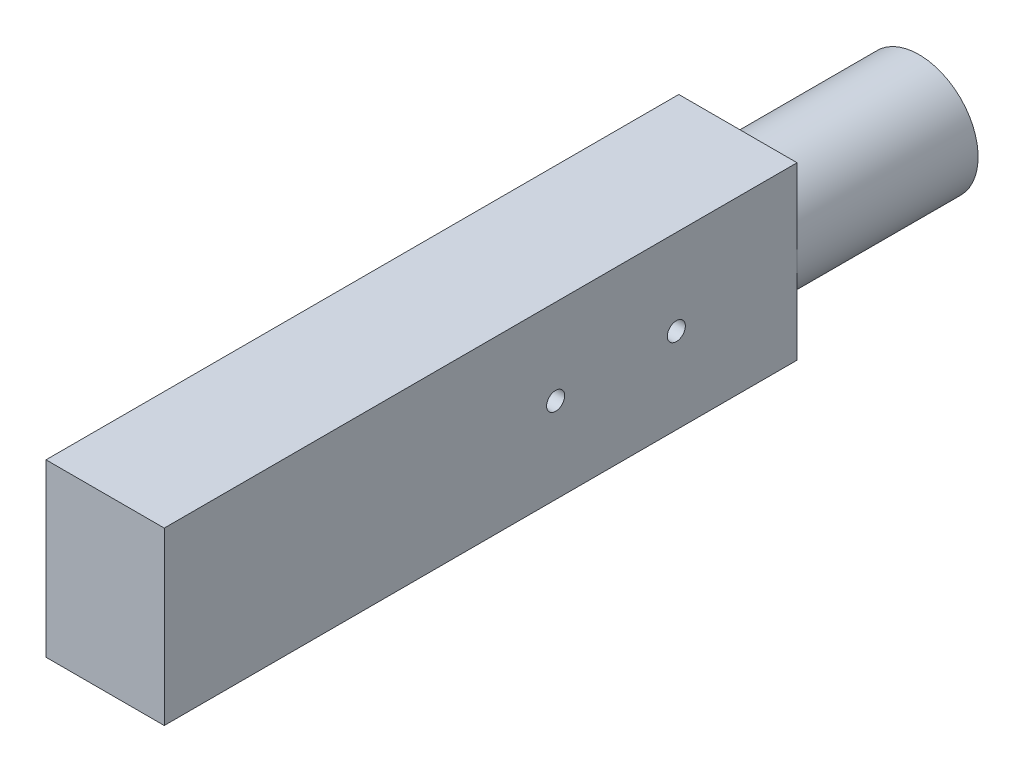
SolidWorks part; units mm, degrees
ref_plane "Front Plane" through (0, 0, 0) normal (0, 0, 1) x (1, 0, 0)
ref_plane "Top Plane" through (0, 0, 0) normal (0, 1, 0) x (1, 0, 0)
ref_plane "Right Plane" through (0, 0, 0) normal (1, 0, 0) x (0, 0, -1)
sketch "Sketch1" plane through (0, 0, 0) normal (0, 0, 1) x (1, 0, 0)
  line L1 (0, 0) -> (19.5934, 0)
  line L2 (0, 0) -> (0, 28.3351)
  line L3 (0, 28.3351) -> (19.5934, 28.3351)
  line L4 (19.5934, 0) -> (19.5934, 28.3351)
  dimension "D1" = 19.5934
  dimension "D2" = 28.3351
extrude "Boss-Extrude1" add sketch "Sketch1" along normal blind 104.8451
sketch "Sketch2" plane through (0, 0, 0) normal (0, 0, -1) x (-1, 0, 0)
  line L0 (-9.7967, 0) -> (-9.7967, 28.3351) construction
  line L1 (0, 0) -> (-19.5934, 0) construction
  line L2 (-19.5934, 28.3351) -> (0, 28.3351) construction
  line L5 (-19.5934, 0) -> (-19.5934, 28.3351) construction
  circle A0 centre (-9.7967, 14.1676) radius 9.7967
  point P9 (-9.7967, 14.1676)
extrude "Boss-Extrude2" add sketch "Sketch2" along normal blind 30
ref_plane "Plane4" through (9.7967, 0, 0) normal (-1, 0, 0) x (0, 0, 1)
sketch "Sketch3" plane through (19.5934, 0, 0) normal (1, 0, 0) x (0, 0, -1)
  line L0 (0, 14.1676) -> (-20, 14.1676) construction
  line L2 (-20, 14.1676) -> (-40, 14.1676) construction
  circle A0 centre (-20, 14.1676) radius 1.5
  circle A1 centre (-40, 14.1676) radius 1.5
  dimension "D1" = 3
  dimension "D2" = 3
  dimension "D3" = 20
  dimension "D4" = 20
extrude "Cut-Extrude1" cut sketch "Sketch3" against normal through all
equation "\"D1@Boss-Extrude1\"= \"LA_length\""
equation "\"LA_width\"=19.59343046"
equation "\"LA_height\"=28.33511482"
equation "\"D1@Sketch1\"=\"LA_width\""
equation "\"D2@Sketch1\"=\"LA_height\""
equation "\"LA_length\"=104.84505691"
equation "\"radius_pin\"=9.79671523"
